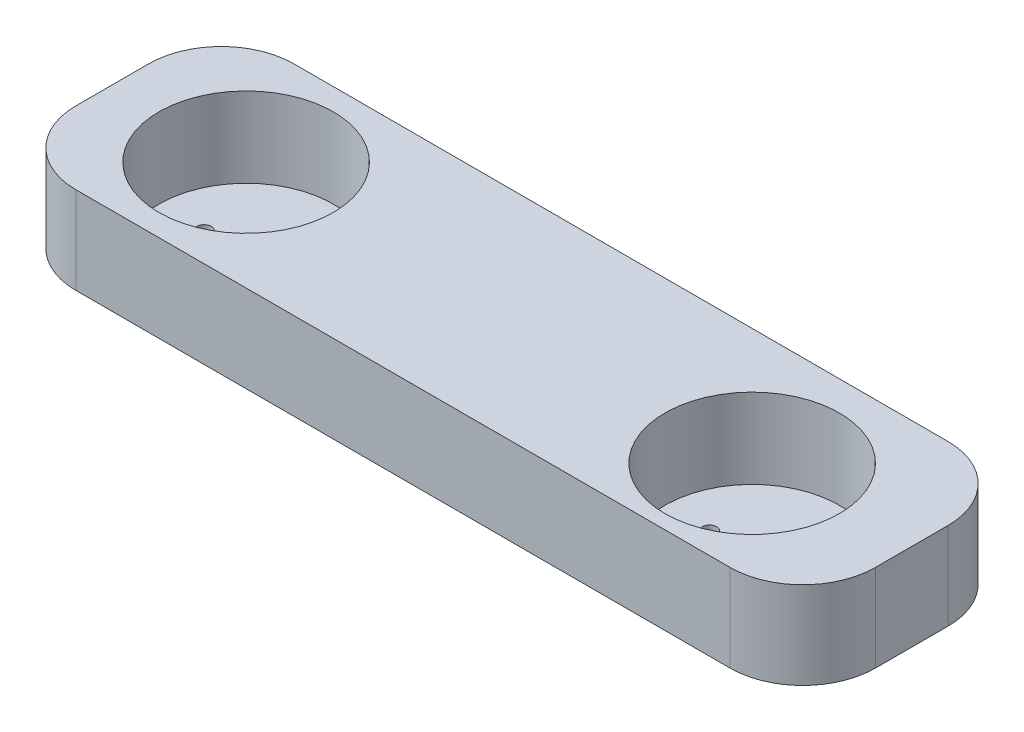
SolidWorks part; units mm, degrees
ref_plane "Front Plane" through (0, 0, 0) normal (0, 0, 1) x (1, 0, 0)
ref_plane "Top Plane" through (0, 0, 0) normal (0, 1, 0) x (1, 0, 0)
ref_plane "Right Plane" through (0, 0, 0) normal (1, 0, 0) x (0, 0, -1)
sketch "Sketch1" plane through (0, 0, 0) normal (0, 1, 0) x (1, 0, 0)
  line L1 (-49.6146, 18.5384) -> (60.3854, 18.5384)
  line L2 (-49.6146, 18.5384) -> (-49.6146, -11.4616)
  line L3 (-49.6146, -11.4616) -> (60.3854, -11.4616)
  line L4 (60.3854, 18.5384) -> (60.3854, -11.4616)
  dimension "D1" = 110
  dimension "D2" = 30
extrude "Boss-Extrude1" add sketch "Sketch1" along normal blind 12
fillet "Fillet1" radius 10 2 edges at (-49.6146, 6, -18.5384) (-49.6146, 6, 11.4616)
fillet "Fillet2" radius 10 2 edges at (60.3854, 6, -18.5384) (60.3854, 6, 11.4616)
sketch "Sketch9" plane through (0, 12, 0) normal (0, 1, 0) x (1, 0, 0)
  line L0 (-39.6146, -11.4616) -> (50.3854, -11.4616) construction
  circle A0 centre (-31.1958, 3.5384) radius 12
  dimension "D1" = 15
extrude "Cut-Extrude5" cut sketch "Sketch9" against normal blind 11
sketch "Sketch13" plane through (70.6968, 12, 1.0722) normal (0, 1, 0) x (1, 0, 0)
  circle A0 centre (-31.1958, 3.5384) radius 12
extrude "Cut-Extrude7" cut sketch "Sketch13" against normal blind 11
sketch "Sketch15" plane through (70.6968, 1, 1.0722) normal (0, 1, 0) x (1, 0, 0)
  circle A0 centre (-31.1477, 3.5384) radius 3.43
  circle A1 centre (-25.2177, 3.5384) radius 1
  circle A2 centre (-37.0777, 3.5384) radius 1
  dimension "D2" = 2.5
  dimension "D3" = 2.5
extrude "Cut-Extrude8" cut sketch "Sketch15" against normal through all
sketch "Sketch16" plane through (70.6968, 1, 1.0722) normal (0, 1, 0) x (1, 0, 0)
  circle A0 centre (-101.6996, 4.5567) radius 3.43
  circle A1 centre (-95.7696, 4.5567) radius 1
  circle A2 centre (-107.6296, 4.5567) radius 1
  dimension "D2" = 2.5
  dimension "D3" = 2.5
extrude "Cut-Extrude9" cut sketch "Sketch16" against normal through all
